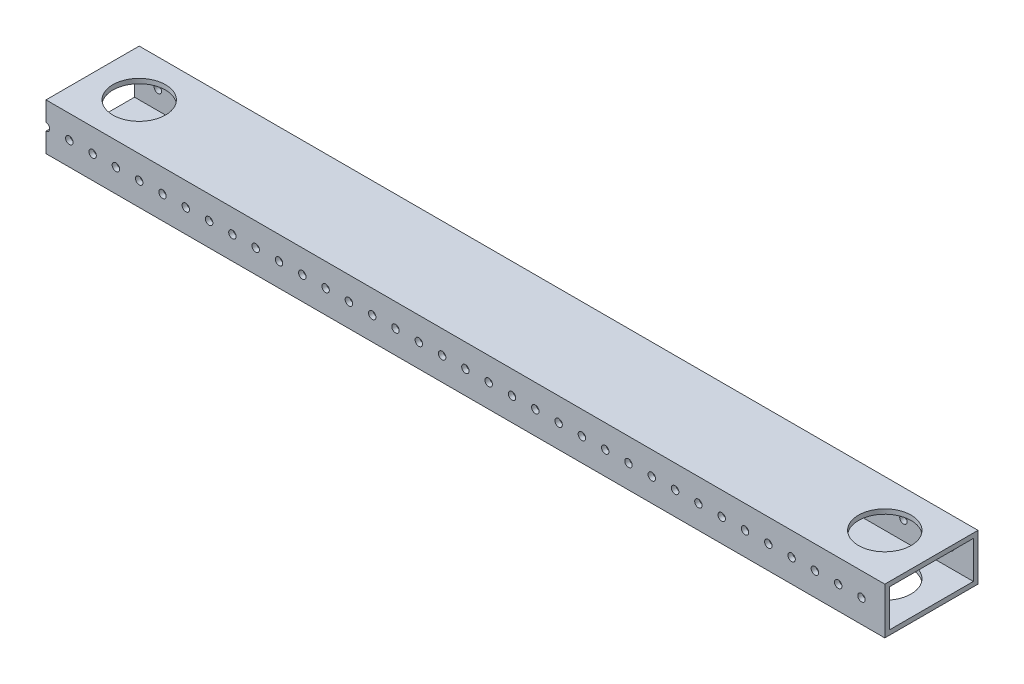
SolidWorks part; units mm, degrees
ref_plane "Front Plane" through (0, 0, 0) normal (0, 0, 1) x (1, 0, 0)
ref_plane "Top Plane" through (0, 0, 0) normal (0, 1, 0) x (1, 0, 0)
ref_plane "Right Plane" through (0, 0, 0) normal (1, 0, 0) x (0, 0, -1)
sketch "Sketch1" plane through (0, 0, 0) normal (1, 0, 0) x (0, 0, -1)
  line L0 (-22.86, 10.16) -> (22.86, 10.16)
  line L1 (-25.4, -12.7) -> (25.4, -12.7)
  line L2 (-25.4, -12.7) -> (-25.4, 12.7)
  line L3 (-25.4, 12.7) -> (25.4, 12.7)
  line L4 (25.4, -12.7) -> (25.4, 12.7)
  line L5 (-25.4, -12.7) -> (25.4, 12.7) construction
  line L6 (-25.4, 12.7) -> (25.4, -12.7) construction
  line L7 (22.86, -10.16) -> (22.86, 10.16)
  line L8 (-22.86, -10.16) -> (22.86, -10.16)
  line L9 (-22.86, -10.16) -> (-22.86, 10.16)
  point P0 (0, 0)
  dimension "D1" = 50.8
  dimension "D2" = 25.4
  dimension "D3" = 2.54
extrude "Boss-Extrude1" add sketch "Sketch1" along normal mid plane 457.2
sketch "Sketch3" plane through (0, -12.7, 0) normal (0, -1, 0) x (1, 0, 0)
  line L0 (228.6, 25.4) -> (228.6, -25.4) construction
  line L1 (0, 0) -> (0, -25.4) construction
  line L2 (228.6, -25.4) -> (-228.6, -25.4) construction
  circle A0 centre (203.2, 0) radius 14.351
  circle A1 centre (-203.2, 0) radius 14.351
  dimension "D1" = 28.702
  dimension "D2" = 25.4
extrude "Cut-Extrude2" cut sketch "Sketch3" against normal through all
sketch "Sketch4" plane through (0, 0, -25.4) normal (0, 0, -1) x (-1, 0, 0)
  line L0 (-228.6, -12.7) -> (-228.6, 12.7) construction
  circle A0 centre (-215.9, 0) radius 2.032
  circle A1 centre (-203.2, 0) radius 2.032
  circle A2 centre (-190.5, 0) radius 2.032
  circle A3 centre (-177.8, 0) radius 2.032
  circle A4 centre (-165.1, 0) radius 2.032
  circle A5 centre (-152.4, 0) radius 2.032
  circle A6 centre (-139.7, 0) radius 2.032
  circle A7 centre (-127, 0) radius 2.032
  circle A8 centre (-114.3, 0) radius 2.032
  circle A9 centre (-101.6, 0) radius 2.032
  circle A10 centre (-88.9, 0) radius 2.032
  circle A11 centre (-76.2, 0) radius 2.032
  circle A12 centre (-63.5, 0) radius 2.032
  circle A13 centre (-50.8, 0) radius 2.032
  circle A14 centre (-38.1, 0) radius 2.032
  circle A15 centre (-25.4, 0) radius 2.032
  circle A16 centre (-12.7, 0) radius 2.032
  circle A17 centre (0, 0) radius 2.032
  circle A18 centre (12.7, 0) radius 2.032
  circle A19 centre (25.4, 0) radius 2.032
  circle A20 centre (38.1, 0) radius 2.032
  circle A21 centre (50.8, 0) radius 2.032
  circle A22 centre (63.5, 0) radius 2.032
  circle A23 centre (76.2, 0) radius 2.032
  circle A24 centre (88.9, 0) radius 2.032
  circle A25 centre (101.6, 0) radius 2.032
  circle A26 centre (114.3, 0) radius 2.032
  circle A27 centre (127, 0) radius 2.032
  circle A28 centre (139.7, 0) radius 2.032
  circle A29 centre (152.4, 0) radius 2.032
  circle A30 centre (165.1, 0) radius 2.032
  circle A31 centre (177.8, 0) radius 2.032
  circle A32 centre (190.5, 0) radius 2.032
  circle A33 centre (203.2, 0) radius 2.032
  circle A34 centre (215.9, 0) radius 2.032
  circle A35 centre (228.6, 0) radius 2.032
  dimension "D1" = 4.064
  dimension "D2" = 12.7
  dimension "D3" = 36
extrude "Cut-Extrude3" cut sketch "Sketch4" against normal through all
